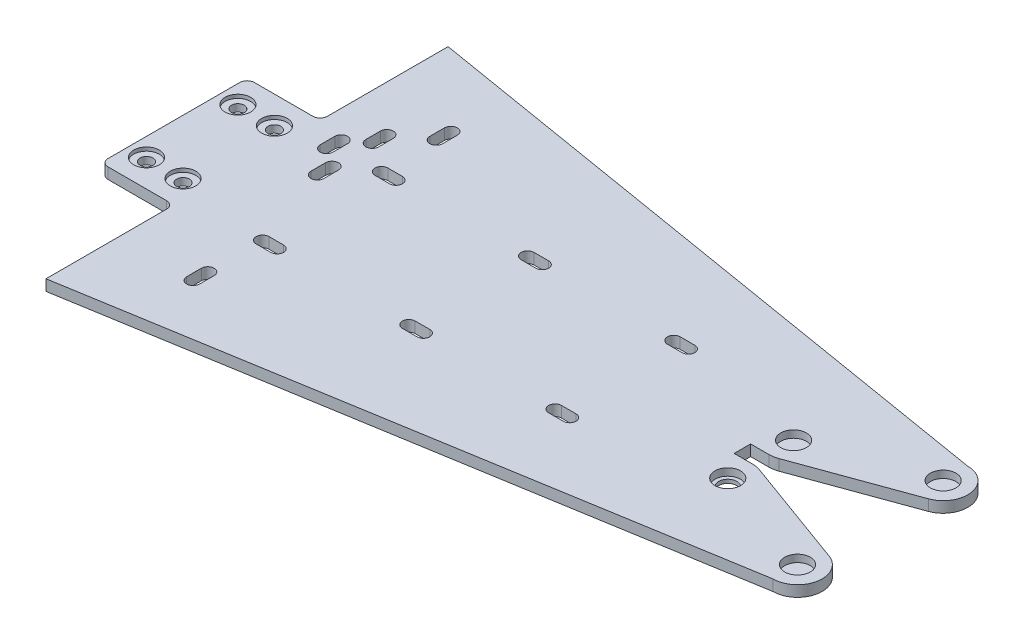
SolidWorks part; units mm, degrees
ref_plane "前视基准面" through (0, 0, 0) normal (0, 0, 1) x (1, 0, 0)
ref_plane "上视基准面" through (0, 0, 0) normal (0, 1, 0) x (1, 0, 0)
ref_plane "右视基准面" through (0, 0, 0) normal (1, 0, 0) x (0, 0, -1)
sketch "草图1" plane through (0, 0, 0) normal (0, 1, 0) x (1, 0, 0)
  line L1 (-17.5, -27.5) -> (17.5, -27.5)
  line L2 (-17.5, -27.5) -> (-17.5, 27.5)
  line L3 (-17.5, 27.5) -> (17.5, 27.5)
  line L4 (17.5, -27.5) -> (17.5, 27.5)
  line L5 (-17.5, -27.5) -> (17.5, 27.5) construction
  line L6 (-17.5, 27.5) -> (17.5, -27.5) construction
  point P0 (0, 0)
  dimension "D1" = 55
  dimension "D2" = 35
extrude "凸台-拉伸1" add sketch "草图1" along normal blind 1
sketch "草图2" plane through (0, 1, 0) normal (0, 1, 0) x (1, 0, 0)
  line L0 (-105.917, 0) -> (-62.25, 0) construction
  line L1 (106.75, 2.25) -> (121.75, 2.25)
  line L2 (-31.4474, 57.1013) -> (151.75, 26.6691)
  line L4 (124.0586, 2.6571) -> (154.0586, 13.5762)
  line L5 (-60.1618, 23.6059) -> (-42.6093, 52.0296)
  line L6 (121.75, 2.25) -> (121.75, 9) construction
  line L7 (121.75, -2.25) -> (121.75, -9) construction
  line L8 (-60.1618, -23.6059) -> (-42.6093, -52.0296)
  line L9 (124.0586, -2.6571) -> (154.0586, -13.5762)
  line L10 (121.75, -9) -> (128.5, -9)
  line L11 (-31.4474, -57.1013) -> (151.75, -26.6691)
  line L12 (106.75, -2.25) -> (121.75, -2.25)
  line L13 (-62.25, 16.25) -> (-62.25, -16.25)
  line L14 (106.75, 2.25) -> (106.75, -2.25)
  line L15 (106.75, 0) -> (124.0666, 0) construction
  arc A0 (-60.1618, 23.6059) -> (-62.25, 16.25) centre (-48.25, 16.25) ccw
  arc A1 (-31.4474, 57.1013) -> (-42.6093, 52.0296) centre (-33.25, 46.25) ccw
  arc A2 (121.75, 2.25) -> (124.0586, 2.6571) centre (121.75, 9) ccw
  arc A3 (154.0586, 13.5762) -> (151.75, 26.6691) centre (151.75, 19.9191) ccw
  arc A4 (154.0586, -13.5762) -> (151.75, -26.6691) centre (151.75, -19.9191) cw
  arc A5 (121.75, -2.25) -> (128.5, -9) centre (121.75, -9) cw
  arc A6 (-31.4474, -57.1013) -> (-42.6093, -52.0296) centre (-33.25, -46.25) cw
  arc A7 (-60.1618, -23.6059) -> (-62.25, -16.25) centre (-48.25, -16.25) cw
  dimension "D2" = 28
  dimension "D3" = 48.25
  dimension "D4" = 22
  dimension "D5" = 15
  dimension "D7" = 13.5
  dimension "D10" = 13.5
  dimension "D11" = 30
  dimension "D1" = 2.25
  dimension "D8" = 20
  dimension "D9" = 30
  dimension "D12" = 15
extrude "凸台-拉伸2" add sketch "草图2" along normal blind 3
sketch "草图3" plane through (0, 4, 0) normal (0, 1, 0) x (1, 0, 0)
  circle A0 centre (-48.25, 16.25) radius 5
  circle A1 centre (-48.25, -16.25) radius 5
  circle A2 centre (-33.25, 46.25) radius 6.6982
  circle A3 centre (151.75, 19.9191) radius 2.5794
  circle A4 centre (121.75, 9) radius 2.5794
  circle A5 centre (121.75, -9) radius 2.5794
  circle A6 centre (151.75, -19.9191) radius 2.5794
  circle A7 centre (-33.25, -46.25) radius 6.6982
  dimension "D1" = 10
extrude "切除-拉伸1" cut sketch "草图3" against normal through all contours A0 | A1
sketch "草图4" plane through (0, 4, 0) normal (0, 1, 0) x (1, 0, 0)
  circle A0 centre (-33.25, 46.25) radius 4
  circle A1 centre (-33.25, -46.25) radius 4
  dimension "D1" = 8
  dimension "D2" = 8
extrude "切除-拉伸2" cut sketch "草图4" against normal blind 2
sketch "草图5" plane through (0, 4, 0) normal (0, 1, 0) x (1, 0, 0)
  circle A0 centre (121.75, 9) radius 2
  circle A1 centre (121.75, -9) radius 2
  circle A2 centre (151.75, 19.9191) radius 2
  circle A3 centre (151.75, -19.9191) radius 2
  dimension "D1" = 4
extrude "切除-拉伸3" cut sketch "草图5" against normal blind 2
sketch "草图8" plane through (0, 1, 0) normal (0, -1, 0) x (1, 0, 0)
  line L1 (-39.75, -26.25) -> (-26.75, -26.25)
  line L2 (-39.75, -26.25) -> (-39.75, -66.25)
  line L3 (-39.75, -66.25) -> (-26.75, -66.25)
  line L4 (-26.75, -26.25) -> (-26.75, -66.25)
  line L5 (-39.75, -26.25) -> (-26.75, -66.25) construction
  line L6 (-39.75, -66.25) -> (-26.75, -26.25) construction
  line L16 (124.0586, 2.6571) -> (154.0586, 13.5762)
  line L17 (151.75, 26.6691) -> (-31.4474, 57.1013)
  line L18 (-42.6093, 52.0296) -> (-60.1618, 23.6059)
  line L19 (-62.25, 16.25) -> (-62.25, -16.25)
  line L20 (-60.1618, -23.6059) -> (-42.6093, -52.0296)
  line L21 (-31.4474, -57.1013) -> (151.75, -26.6691)
  line L22 (154.0586, -13.5762) -> (124.0586, -2.6571)
  line L23 (121.75, -2.25) -> (106.75, -2.25)
  line L24 (106.75, -2.25) -> (106.75, 2.25)
  line L25 (106.75, 2.25) -> (121.75, 2.25)
  line L26 (124.0586, 2.6571) -> (154.0586, 13.5762)
  line L27 (151.75, 26.6691) -> (-31.4474, 57.1013)
  line L28 (-42.6093, 52.0296) -> (-60.1618, 23.6059)
  line L31 (-31.4474, -57.1013) -> (151.75, -26.6691)
  line L32 (154.0586, -13.5762) -> (124.0586, -2.6571)
  line L33 (121.75, -2.25) -> (106.75, -2.25)
  line L34 (106.75, -2.25) -> (106.75, 2.25)
  line L35 (106.75, 2.25) -> (121.75, 2.25)
  arc A8 (154.0586, 13.5762) -> (151.75, 26.6691) centre (151.75, 19.9191) ccw
  arc A9 (-31.4474, 57.1013) -> (-42.6093, 52.0296) centre (-33.25, 46.25) ccw
  arc A10 (-60.1618, 23.6059) -> (-62.25, 16.25) centre (-48.25, 16.25) ccw
  arc A11 (-62.25, -16.25) -> (-60.1618, -23.6059) centre (-48.25, -16.25) ccw
  arc A12 (-42.6093, -52.0296) -> (-31.4474, -57.1013) centre (-33.25, -46.25) ccw
  arc A13 (151.75, -26.6691) -> (154.0586, -13.5762) centre (151.75, -19.9191) ccw
  arc A14 (124.0586, -2.6571) -> (121.75, -2.25) centre (121.75, -9) ccw
  arc A15 (121.75, 2.25) -> (124.0586, 2.6571) centre (121.75, 9) ccw
  arc A16 (154.0586, 13.5762) -> (151.75, 26.6691) centre (151.75, 19.9191) ccw
  arc A17 (-31.4474, 57.1013) -> (-42.6093, 52.0296) centre (-33.25, 46.25) ccw
  arc A18 (-60.1618, 23.6059) -> (-62.25, 16.25) centre (-48.25, 16.25) ccw
  arc A19 (-62.25, -16.25) -> (-60.1618, -23.6059) centre (-48.25, -16.25) ccw
  arc A20 (-42.6093, -52.0296) -> (-31.4474, -57.1013) centre (-33.25, -46.25) ccw
  arc A21 (151.75, -26.6691) -> (154.0586, -13.5762) centre (151.75, -19.9191) ccw
  arc A22 (124.0586, -2.6571) -> (121.75, -2.25) centre (121.75, -9) ccw
  arc A23 (121.75, 2.25) -> (124.0586, 2.6571) centre (121.75, 9) ccw
  point P0 (-33.25, -46.25)
  arc M32 (-42.6093, -52.0296) -> (-31.4474, -57.1013) centre (-33.25, -46.25) ccw
  line M33 (-31.4474, -57.1013) -> (151.75, -26.6691)
  dimension "D1" = 13
  dimension "D2" = 40
  dimension "D3" = 0
extrude "凸台-拉伸3" add sketch "草图8" along normal blind 7 contours L4 L1 L2 M32 M33
mirror "镜向1" about plane through (0, 0, 0) normal (0, 0, 1) of "凸台-拉伸3"
sketch "草图9" plane through (0, -6, 0) normal (0, -1, 0) x (1, 0, 0)
  line L0 (-39.75, -26.25) -> (-26.75, -26.25) construction
  line L2 (-38.25, -53.75) -> (-38.25, -27.75)
  line L3 (-38.25, -27.75) -> (-28.25, -27.75)
  line L4 (-28.25, -53.75) -> (-28.25, -27.75)
  line L5 (-35.5448, -54.7408) -> (-28.25, -27.75) construction
  line L6 (-38.25, -27.75) -> (-31.223, -53.75) construction
  line L8 (-28.25, -53.75) -> (-38.25, -53.75)
  point P0 (-33.25, -46.25)
  dimension "D1" = 10
  dimension "D2" = 1.5
  dimension "D3" = 26
extrude "切除-拉伸4" cut sketch "草图9" against normal through all from offset 1.5 offset against normal yes
mirror "镜向2" about plane through (0, 0, 0) normal (0, 0, 1) of "切除-拉伸4"
sketch "草图10" plane through (0, 0, -53.75) normal (0, 0, 1) x (1, 0, 0)
  line L4 (-38.25, -4.5) -> (-28.25, -4.5)
  line L5 (-28.25, -4.5) -> (-28.25, 4)
  line L6 (-28.25, 4) -> (-38.25, 4)
  line L7 (-38.25, 4) -> (-38.25, -4.5)
  line L8 (-38.25, -4.5) -> (-28.25, -4.5)
  line L9 (-28.25, -4.5) -> (-28.25, 4)
  line L10 (-28.25, 4) -> (-38.25, 4)
  line L11 (-38.25, 4) -> (-38.25, -4.5)
  circle A0 centre (-33.25, -1.5) radius 1.5
  dimension "D2" = 3
  dimension "D3" = 3
  dimension "D1" = 0
extrude "切除-拉伸5" cut sketch "草图10" against normal through all contours A0
mirror "镜向3" about plane through (0, 0, 0) normal (0, 0, 1) of "切除-拉伸5"
sketch "草图11" plane through (0, 4, 0) normal (0, 1, 0) x (1, 0, 0)
  line L0 (-62.25, 16.25) -> (-62.25, 50.4199)
  line L1 (-62.25, -16.25) -> (-62.25, -50.4199)
  line L10 (154.0586, -13.5762) -> (124.0586, -2.6571)
  line L11 (121.75, -2.25) -> (106.75, -2.25)
  line L12 (106.75, -2.25) -> (106.75, 2.25)
  line L13 (106.75, 2.25) -> (121.75, 2.25)
  line L14 (124.0586, 2.6571) -> (154.0586, 13.5762)
  line L15 (151.75, 26.6691) -> (-31.4474, 57.1013)
  line L16 (-42.6093, 52.0296) -> (-60.1618, 23.6059)
  line L17 (-62.25, 16.25) -> (-62.25, -16.25)
  line L18 (-60.1618, -23.6059) -> (-42.6093, -52.0296)
  line L19 (-31.4474, -57.1013) -> (151.75, -26.6691)
  line L20 (154.0586, -13.5762) -> (124.0586, -2.6571)
  line L21 (121.75, -2.25) -> (106.75, -2.25)
  line L22 (106.75, -2.25) -> (106.75, 2.25)
  line L23 (106.75, 2.25) -> (121.75, 2.25)
  line L24 (124.0586, 2.6571) -> (154.0586, 13.5762)
  line L25 (151.75, 26.6691) -> (-50.6113, 60.2847)
  line L26 (-42.6093, 52.0296) -> (-60.1618, 23.6059)
  line L27 (-62.25, 16.25) -> (-62.25, -16.25)
  line L28 (-60.1618, -23.6059) -> (-42.6093, -52.0296)
  line L29 (-50.6113, -60.2847) -> (151.75, -26.6691)
  arc A0 (-62.25, -50.4199) -> (-50.6113, -60.2847) centre (-52.25, -50.4199) ccw
  arc A1 (-50.6113, 60.2847) -> (-62.25, 50.4199) centre (-52.25, 50.4199) ccw
  arc A8 (124.0586, -2.6571) -> (121.75, -2.25) centre (121.75, -9) ccw
  arc A9 (121.75, 2.25) -> (124.0586, 2.6571) centre (121.75, 9) ccw
  arc A10 (154.0586, 13.5762) -> (151.75, 26.6691) centre (151.75, 19.9191) ccw
  arc A11 (-31.4474, 57.1013) -> (-42.6093, 52.0296) centre (-33.25, 46.25) ccw
  arc A12 (-60.1618, 23.6059) -> (-62.25, 16.25) centre (-48.25, 16.25) ccw
  arc A13 (-62.25, -16.25) -> (-60.1618, -23.6059) centre (-48.25, -16.25) ccw
  arc A14 (-42.6093, -52.0296) -> (-31.4474, -57.1013) centre (-33.25, -46.25) ccw
  arc A15 (151.75, -26.6691) -> (154.0586, -13.5762) centre (151.75, -19.9191) ccw
  arc A16 (124.0586, -2.6571) -> (121.75, -2.25) centre (121.75, -9) ccw
  arc A17 (121.75, 2.25) -> (124.0586, 2.6571) centre (121.75, 9) ccw
  arc A18 (154.0586, 13.5762) -> (151.75, 26.6691) centre (151.75, 19.9191) ccw
  arc A19 (-31.4474, 57.1013) -> (-42.6093, 52.0296) centre (-33.25, 46.25) ccw
  arc A20 (-60.1618, 23.6059) -> (-62.25, 16.25) centre (-48.25, 16.25) ccw
  arc A21 (-62.25, -16.25) -> (-60.1618, -23.6059) centre (-48.25, -16.25) ccw
  arc A22 (-42.6093, -52.0296) -> (-31.4474, -57.1013) centre (-33.25, -46.25) ccw
  arc A23 (151.75, -26.6691) -> (154.0586, -13.5762) centre (151.75, -19.9191) ccw
  arc M28 (-31.4474, 57.1013) -> (-42.6093, 52.0296) centre (-33.25, 46.25) ccw
  line M29 (-42.6093, 52.0296) -> (-60.1618, 23.6059)
  arc M30 (-60.1618, 23.6059) -> (-62.25, 16.25) centre (-48.25, 16.25) ccw
  arc M32 (-62.25, -16.25) -> (-60.1618, -23.6059) centre (-48.25, -16.25) ccw
  line M33 (-60.1618, -23.6059) -> (-42.6093, -52.0296)
  arc M34 (-42.6093, -52.0296) -> (-31.4474, -57.1013) centre (-33.25, -46.25) ccw
  dimension "D2" = 10
  dimension "D3" = 10
  dimension "D1" = 0
extrude "凸台-拉伸4" add sketch "草图11" against normal up to surface (3 mm away) contours L25 A1 L0 M30 M29 M28 | L1 A0 L29 M34 M33 M32 up to face at (0, 1, 0)
sketch "草图12" plane through (0, 1, 0) normal (0, -1, 0) x (1, 0, 0)
  circle A0 centre (-48.25, 16.25) radius 9
  circle A1 centre (-48.25, -16.25) radius 9
  circle A2 centre (-48.25, 16.25) radius 5 construction
  circle A3 centre (-48.25, 16.25) radius 5
  circle A4 centre (-48.25, -16.25) radius 5 construction
  circle A5 centre (-48.25, -16.25) radius 5
  dimension "D1" = 18
  dimension "D2" = 18
extrude "凸台-拉伸5" add sketch "草图12" along normal blind 2.5
sketch "草图13" plane through (0, 4, 0) normal (0, 1, 0) x (1, 0, 0)
  circle A0 centre (-48.25, 16.25) radius 7.5
  circle A1 centre (-48.25, -16.25) radius 7.5
  dimension "D1" = 15
  dimension "D2" = 15
extrude "切除-拉伸6" cut sketch "草图13" against normal blind 4
sketch "草图14" plane through (0, 4, 0) normal (0, 1, 0) x (1, 0, 0)
  line L0 (-45.75, 61.25) -> (-45.75, 27.75)
  line L2 (-20.75, 27.75) -> (-20.75, 61.25)
  line L3 (-20.75, 61.25) -> (-45.75, 61.25)
  line L4 (-28.25, 27.75) -> (-28.25, 53.75)
  line L5 (-28.25, 53.75) -> (-38.25, 53.75)
  line L6 (-38.25, 53.75) -> (-38.25, 27.75)
  line L7 (-38.25, 27.75) -> (-28.25, 27.75)
  line L8 (-28.25, 27.75) -> (-28.25, 53.75)
  line L9 (-28.25, 53.75) -> (-38.25, 53.75)
  line L10 (-38.25, 53.75) -> (-38.25, 27.75)
  line L11 (-45.75, 27.75) -> (-20.75, 27.75)
  line L12 (-38.25, 27.75) -> (-28.25, 27.75) construction
  line L13 (-45.75, 61.25) -> (-45.75, 20.25) construction
  line L14 (-20.75, 20.25) -> (-20.75, 61.25) construction
  line L15 (-45.75, 20.25) -> (-20.75, 20.25) construction
  line M19 (151.75, 26.6691) -> (-50.6113, 60.2847)
  line M25 (-28.25, 53.75) -> (-28.25, 27.75)
  line M26 (-28.25, 27.75) -> (-38.25, 27.75)
  line M27 (-38.25, 27.75) -> (-38.25, 53.75)
  line M28 (-38.25, 53.75) -> (-28.25, 53.75)
  dimension "D1" = 0
  dimension "D2" = 7.5
extrude "切除-拉伸7" cut sketch "草图14" against normal blind 2 contours M25 M28 M27 M26 | L0 L11 L2 M27 M28 M25 M19
sketch "草图15" plane through (0, 2, 0) normal (0, 1, 0) x (1, 0, 0)
  line L8 (-28.25, 53.75) -> (-28.25, 27.75)
  line L9 (-28.25, 27.75) -> (-20.75, 27.75)
  line L10 (-20.75, 27.75) -> (-20.75, 55.3243)
  line L11 (-20.75, 55.3243) -> (-45.75, 59.4772)
  line L12 (-45.75, 59.4772) -> (-45.75, 27.75)
  line L13 (-45.75, 27.75) -> (-38.25, 27.75)
  line L14 (-38.25, 27.75) -> (-38.25, 53.75)
  line L15 (-38.25, 53.75) -> (-28.25, 53.75)
  line L19 (-18.75, 54.992) -> (-47.75, 59.8094)
  line L23 (-38.25, 53.75) -> (-28.25, 53.75)
  line L32 (-30.25, 51.75) -> (-30.25, 25.75)
  line L33 (-30.25, 25.75) -> (-18.75, 25.75)
  line L34 (-18.75, 25.75) -> (-18.75, 57.0195)
  line L35 (-18.75, 57.0195) -> (-47.75, 61.8368)
  line L36 (-47.75, 61.8368) -> (-47.75, 25.75)
  line L37 (-47.75, 25.75) -> (-36.25, 25.75)
  line L38 (-36.25, 25.75) -> (-36.25, 51.75)
  line L39 (-36.25, 51.75) -> (-30.25, 51.75)
  line L41 (-30.25, 25.75) -> (-18.75, 25.75)
  line L42 (-18.75, 25.75) -> (-18.75, 54.992)
  line L44 (-47.75, 59.8094) -> (-47.75, 25.75)
  line L45 (-47.75, 25.75) -> (-30.25, 25.75)
  dimension "D1" = 0
  dimension "D2" = 2
extrude "凸台-拉伸6" add sketch "草图15" against normal blind 2 from surface at -1 contours L44 L45 L41 L42 L19 starting at face at (-48.25, 1, 25.25)
sketch "草图16" plane through (0, -6, 0) normal (0, -1, 0) x (1, 0, 0)
  line L0 (-39.75, -55.1241) -> (-39.75, -65.9532)
  line L1 (-39.75, -65.9532) -> (-26.75, -64.7485)
  line L2 (-26.75, -64.7485) -> (-26.75, -56.321)
  line L4 (-26.75, -56.321) -> (-26.75, -26.25)
  line L5 (-26.75, -26.25) -> (-39.75, -26.25)
  line L6 (-39.75, -26.25) -> (-39.75, -55.1241)
  line L7 (-31.4474, -57.1013) -> (-26.75, -56.321)
  line L8 (-26.75, -56.321) -> (-26.75, -26.25)
  line L9 (-26.75, -26.25) -> (-39.75, -26.25)
  line L10 (-39.75, -26.25) -> (-39.75, -55.1241)
  line L11 (-31.4474, -57.1013) -> (-26.75, -56.321)
  arc A1 (-39.75, -55.1241) -> (-31.4474, -57.1013) centre (-33.25, -46.25) ccw
  arc A2 (-39.75, -55.1241) -> (-31.4474, -57.1013) centre (-33.25, -46.25) ccw
  line M6 (-26.75, -56.321) -> (-26.75, -26.25)
  line M7 (-26.75, -26.25) -> (-39.75, -26.25)
  line M8 (-39.75, -26.25) -> (-39.75, -55.1241)
  arc M9 (-39.75, -55.1241) -> (-31.4474, -57.1013) centre (-33.25, -46.25) ccw
  line M10 (-31.4474, -57.1013) -> (-26.75, -56.321)
  dimension "D1" = 0
extrude "切除-拉伸8" cut sketch "草图16" against normal through all contours M10 M6 M7 M8 M9 | L1 L2 L0 M10 M9
mirror "镜向4" about plane through (0, 0, 0) normal (0, 0, 1) of "切除-拉伸7", "切除-拉伸4", "凸台-拉伸6", "切除-拉伸8"
sketch "草图17" plane through (0, 0, 0) normal (0, -1, 0) x (1, 0, 0)
  line L4 (17.5, -27.5) -> (17.5, 27.5)
  line L5 (17.5, 27.5) -> (-17.5, 27.5)
  line L6 (-17.5, 27.5) -> (-17.5, -27.5)
  line L7 (-17.5, -27.5) -> (17.5, -27.5)
  line L8 (17.5, -27.5) -> (17.5, 27.5)
  line L9 (17.5, 27.5) -> (-17.5, 27.5)
  line L10 (-17.5, 27.5) -> (-17.5, -27.5)
  line L11 (-17.5, -27.5) -> (17.5, -27.5)
  dimension "D1" = 0
extrude "切除-拉伸9" cut sketch "草图17" against normal up to surface (1 mm away) up to face at (-48.25, 1, -7.25)
sketch "草图19" plane through (0, 1, 0) normal (0, -1, 0) x (1, 0, 0)
  line L8 (-47.75, -59.8094) -> (-39.75, -58.4805)
  line L9 (-39.75, -58.4805) -> (-39.75, -26.25)
  line L10 (-39.75, -26.25) -> (-26.75, -26.25)
  line L11 (-26.75, -26.25) -> (-26.75, -56.321)
  line L12 (-26.75, -56.321) -> (-18.75, -54.992)
  line L13 (-18.75, -54.992) -> (-18.75, -25.75)
  line L14 (-18.75, -25.75) -> (-47.75, -25.75)
  line L15 (-47.75, -25.75) -> (-47.75, -59.8094)
  line L16 (-18.75, 54.992) -> (-18.75, 25.75)
  line L17 (-18.75, 25.75) -> (-47.75, 25.75)
  line L18 (-47.75, 25.75) -> (-47.75, 59.8094)
  line L19 (-47.75, 59.8094) -> (-50.6113, 60.2847)
  line L20 (-62.25, 50.4199) -> (-62.25, -50.4199)
  line L21 (-50.6113, -60.2847) -> (-47.75, -59.8094)
  line L22 (-47.75, -59.8094) -> (-47.75, -25.75)
  line L23 (-47.75, -25.75) -> (-18.75, -25.75)
  line L24 (-18.75, -25.75) -> (-18.75, -54.992)
  line L25 (-18.75, -54.992) -> (151.75, -26.6691)
  line L26 (154.0586, -13.5762) -> (124.0586, -2.6571)
  line L27 (121.75, -2.25) -> (106.75, -2.25)
  line L28 (106.75, -2.25) -> (106.75, 2.25)
  line L29 (106.75, 2.25) -> (121.75, 2.25)
  line L30 (124.0586, 2.6571) -> (154.0586, 13.5762)
  line L31 (151.75, 26.6691) -> (-18.75, 54.992)
  line L32 (-18.75, 54.992) -> (-18.75, -25.75)
  line L35 (-47.75, 59.8094) -> (-50.6113, 60.2847)
  line L36 (-62.25, 50.4199) -> (-62.25, -50.4199)
  line L37 (-50.6113, -60.2847) -> (-47.75, -59.8094)
  line L40 (-18.75, -25.75) -> (-18.75, -54.992)
  line L48 (-47.75, -59.8094) -> (-39.75, -58.4805)
  line L49 (-39.75, -58.4805) -> (-39.75, -26.25)
  line L50 (-39.75, -26.25) -> (-26.75, -26.25)
  line L51 (-26.75, -26.25) -> (-26.75, -56.321)
  line L52 (-26.75, -56.321) -> (-18.75, -54.992)
  line L53 (-18.75, -54.992) -> (-18.75, -25.75)
  line L56 (-39.75, 26.25) -> (-39.75, 58.4805)
  line L57 (-39.75, 58.4805) -> (-47.75, 59.8094)
  line L58 (-47.75, 59.8094) -> (-47.75, 25.75)
  line L59 (-47.75, 25.75) -> (-18.75, 25.75)
  line L60 (-18.75, 25.75) -> (-18.75, 54.992)
  line L61 (-18.75, 54.992) -> (-26.75, 56.321)
  line L62 (-26.75, 56.321) -> (-26.75, 26.25)
  line L63 (-26.75, 26.25) -> (-39.75, 26.25)
  line L64 (-39.75, 26.25) -> (-39.75, 58.4805)
  line L65 (-39.75, 58.4805) -> (-47.75, 59.8094)
  line L68 (-18.75, 25.75) -> (-18.75, 54.992)
  line L69 (-18.75, 54.992) -> (-26.75, 56.321)
  line L70 (-26.75, 56.321) -> (-26.75, 26.25)
  line L71 (-26.75, 26.25) -> (-39.75, 26.25)
  circle A0 centre (-48.25, 16.25) radius 5 construction
  circle A1 centre (-48.25, 16.25) radius 5
  circle A2 centre (-48.25, -16.25) radius 5 construction
  circle A3 centre (-48.25, -16.25) radius 5
  arc A6 (-50.6113, 60.2847) -> (-62.25, 50.4199) centre (-52.25, 50.4199) ccw
  arc A7 (-62.25, -50.4199) -> (-50.6113, -60.2847) centre (-52.25, -50.4199) ccw
  arc A8 (151.75, -26.6691) -> (154.0586, -13.5762) centre (151.75, -19.9191) ccw
  arc A9 (124.0586, -2.6571) -> (121.75, -2.25) centre (121.75, -9) ccw
  arc A10 (121.75, 2.25) -> (124.0586, 2.6571) centre (121.75, 9) ccw
  arc A11 (154.0586, 13.5762) -> (151.75, 26.6691) centre (151.75, 19.9191) ccw
  arc A12 (-50.6113, 60.2847) -> (-62.25, 50.4199) centre (-52.25, 50.4199) ccw
  arc A13 (-62.25, -50.4199) -> (-50.6113, -60.2847) centre (-52.25, -50.4199) ccw
  circle M23 centre (-48.25, -16.25) radius 9
  circle M24 centre (-48.25, 16.25) radius 9
  line M25 (-18.75, 54.992) -> (-18.75, 25.75)
  line M26 (-18.75, 25.75) -> (-47.75, 25.75)
  line M27 (-47.75, 25.75) -> (-47.75, 59.8094)
  line M28 (-47.75, 59.8094) -> (-50.6113, 60.2847)
  arc M29 (-50.6113, 60.2847) -> (-62.25, 50.4199) centre (-52.25, 50.4199) ccw
  line M30 (-62.25, 50.4199) -> (-62.25, -50.4199)
  arc M31 (-62.25, -50.4199) -> (-50.6113, -60.2847) centre (-52.25, -50.4199) ccw
  line M32 (-50.6113, -60.2847) -> (-47.75, -59.8094)
  line M33 (-47.75, -59.8094) -> (-47.75, -25.75)
  line M34 (-47.75, -25.75) -> (-18.75, -25.75)
  line M35 (-18.75, -25.75) -> (-18.75, -54.992)
  dimension "D1" = 0
  dimension "D2" = 0
  dimension "D3" = 0
extrude "凸台-拉伸8" add sketch "草图19" along direction (0, -1, 0) on the side of the normal up to surface (2.5 mm away) contours L32 M26 M27 M28 M29 M30 M31 M32 M33 M34 M24 M23 | L70 L71 L64 L65 L69 M27 M26 M25 | L51 L52 L48 L49 L50 M35 M34 M33
sketch "草图20" plane through (0, 4, 0) normal (0, 1, 0) x (1, 0, 0)
  line L0 (-39.75, 27.75) -> (-26.75, 27.75)
  line L1 (-26.75, 27.75) -> (-26.75, 26.25)
  line L2 (-26.75, 26.25) -> (-39.75, 26.25)
  line L3 (-39.75, 26.25) -> (-39.75, 27.75) construction
  line L4 (-26.75, 26.25) -> (-39.75, 26.25) construction
  line L5 (-39.75, 26.25) -> (-39.75, 27.75)
  line L6 (-39.75, -26.25) -> (-39.75, -27.75)
  line L7 (-39.75, -27.75) -> (-26.75, -27.75)
  line L8 (-26.75, -27.75) -> (-26.75, -26.25)
  line L9 (-26.75, -26.25) -> (-39.75, -26.25)
  line M7 (-39.75, -26.25) -> (-26.75, -26.25)
  line M8 (-26.75, -26.25) -> (-26.75, -27.75)
  line M24 (-26.75, 27.75) -> (-26.75, 26.25)
  line M25 (-26.75, 26.25) -> (-39.75, 26.25)
  line M26 (-39.75, 26.25) -> (-39.75, 27.75)
  line M36 (-39.75, -27.75) -> (-39.75, -26.25)
extrude "凸台-拉伸9" add sketch "草图20" against normal up to surface (5.5 mm away) contours L0 M26 M25 M24 | L7 M36 M8 M7 up to face at (-48.25, -1.5, 11.25)
sketch "草图21" plane through (0, 4, 0) normal (0, 1, 0) x (1, 0, 0)
  circle A0 centre (121.75, 9) radius 3.5
  circle A1 centre (121.75, -9) radius 3.5
  circle A2 centre (151.75, -19.9191) radius 3.5
  circle A3 centre (151.75, 19.9191) radius 3.5
  dimension "D1" = 7
  dimension "D2" = 7
  dimension "D3" = 7
  dimension "D4" = 7
extrude "切除-拉伸10" cut sketch "草图21" against normal up to surface (2 mm away) up to face at (121.75, 2, -7)
sketch "草图22" plane through (0, 4, 0) normal (0, 1, 0) x (1, 0, 0)
  line L0 (-48.25, 16.25) -> (79.7875, 16.25)
  line L1 (1.75, 16.25) -> (5.75, 16.25) construction
  line L2 (1.75, 18) -> (5.75, 18)
  line L3 (1.75, 14.5) -> (5.75, 14.5)
  line L4 (41.75, 16.25) -> (45.75, 16.25) construction
  line L5 (41.75, 18) -> (45.75, 18)
  line L6 (41.75, 14.5) -> (45.75, 14.5)
  line L7 (81.75, 16.25) -> (85.75, 16.25) construction
  line L8 (81.75, 18) -> (85.75, 18)
  line L9 (81.75, 14.5) -> (85.75, 14.5)
  line L10 (1.75, 31.25) -> (1.75, 35.25) construction
  line L11 (0, 31.25) -> (0, 35.25)
  line L12 (3.5, 31.25) -> (3.5, 35.25)
  line L13 (-3.025, 0) -> (3.025, 0) construction
  line L14 (1.75, -16.25) -> (5.75, -16.25) construction
  line L15 (1.75, -18) -> (5.75, -18)
  line L16 (1.75, -14.5) -> (5.75, -14.5)
  line L17 (41.75, -16.25) -> (45.75, -16.25) construction
  line L18 (41.75, -18) -> (45.75, -18)
  line L19 (41.75, -14.5) -> (45.75, -14.5)
  line L20 (81.75, -16.25) -> (85.75, -16.25) construction
  line L21 (81.75, -18) -> (85.75, -18)
  line L22 (81.75, -14.5) -> (85.75, -14.5)
  line L23 (1.75, -31.25) -> (1.75, -35.25) construction
  line L24 (0, -31.25) -> (0, -35.25)
  line L25 (3.5, -31.25) -> (3.5, -35.25)
  arc A0 (1.75, 18) -> (1.75, 14.5) centre (1.75, 16.25) ccw
  arc A1 (5.75, 14.5) -> (5.75, 18) centre (5.75, 16.25) ccw
  arc A2 (41.75, 18) -> (41.75, 14.5) centre (41.75, 16.25) ccw
  arc A3 (45.75, 14.5) -> (45.75, 18) centre (45.75, 16.25) ccw
  arc A4 (81.75, 18) -> (81.75, 14.5) centre (81.75, 16.25) ccw
  arc A5 (85.75, 14.5) -> (85.75, 18) centre (85.75, 16.25) ccw
  arc A6 (0, 31.25) -> (3.5, 31.25) centre (1.75, 31.25) ccw
  arc A7 (3.5, 35.25) -> (0, 35.25) centre (1.75, 35.25) ccw
  arc A8 (1.75, -18) -> (1.75, -14.5) centre (1.75, -16.25) cw
  arc A9 (5.75, -14.5) -> (5.75, -18) centre (5.75, -16.25) cw
  arc A10 (41.75, -18) -> (41.75, -14.5) centre (41.75, -16.25) cw
  arc A11 (45.75, -14.5) -> (45.75, -18) centre (45.75, -16.25) cw
  arc A12 (81.75, -18) -> (81.75, -14.5) centre (81.75, -16.25) cw
  arc A13 (85.75, -14.5) -> (85.75, -18) centre (85.75, -16.25) cw
  arc A14 (0, -31.25) -> (3.5, -31.25) centre (1.75, -31.25) cw
  arc A15 (3.5, -35.25) -> (0, -35.25) centre (1.75, -35.25) cw
  point P5 (3.75, 16.25)
  point P10 (43.75, 16.25)
  point P17 (83.75, 16.25)
  point P26 (1.75, 33.25)
  point P35 (3.75, -16.25)
  point P42 (43.75, -16.25)
  point P49 (83.75, -16.25)
  point P56 (1.75, -33.25)
  dimension "D1" = 3.5
  dimension "D8" = 40
  dimension "D9" = 40
  dimension "D2" = 4
  dimension "D3" = 4
  dimension "D4" = 4
  dimension "D5" = 3.5
  dimension "D6" = 3.5
  dimension "D7" = 50
  dimension "D10" = 3.5
  dimension "D11" = 4
  dimension "D12" = 15
extrude "切除-拉伸11" cut sketch "草图22" against normal blind 10 contours A9 L16 A8 L15 | A13 L22 A12 L21 | L12 A7 L11 A6 | L3 A1 L0 A0 | L9 A5 L8 A4 | L0 A1 L2 A0 | L25 A15 L24 A14 | L18 A11 L19 A10 | L6 A3 L5 A2
sketch "草图23" plane through (0, 4, 0) normal (0, 1, 0) x (1, 0, 0)
  line L0 (-39.75, 27.75) -> (-45.75, 27.75)
  line L1 (-20.75, 27.75) -> (-45.75, 27.75) construction
  line L2 (-39.75, 27.75) -> (-45.75, 27.75) construction
  line L3 (-26.75, 27.75) -> (-20.75, 27.75)
  line L4 (-20.75, 27.75) -> (-26.75, 27.75) construction
  arc A0 (-50.6113, 60.2847) -> (-62.25, 50.4199) centre (-52.25, 50.4199) ccw construction
  arc A1 (-50.6113, 60.2847) -> (-62.25, 50.4199) centre (-52.25, 50.4199) ccw
  circle A2 centre (-48.25, 16.25) radius 5 construction
  circle A3 centre (-42.75, 32.75) radius 1.75
  circle A4 centre (-23.75, 32.75) radius 1.75
  circle A5 centre (-23.75, 42.75) radius 1.75
  circle A6 centre (-42.75, 42.75) radius 1.75
  dimension "D2" = 3.5
  dimension "D3" = 3.5
  dimension "D4" = 3.5
  dimension "D5" = 3.5
  dimension "D6" = 5
  dimension "D7" = 10
  dimension "D8" = 10
  dimension "D9" = 5
  dimension "D1" = 34.1699
extrude "切除-拉伸12" cut sketch "草图23" against normal blind 10 contours A6 | A3 | A4 | A5
mirror "镜向5" about plane through (0, 0, 0) normal (0, 0, 1) of "切除-拉伸12"
sketch "草图25" plane through (0, 4, 0) normal (0, 1, 0) x (1, 0, 0)
  circle A0 centre (-52.25, -50.4199) radius 1.75
  circle A1 centre (-52.25, 50.4199) radius 1.75
  dimension "D1" = 3.5
  dimension "D2" = 3.5
extrude "切除-拉伸14" cut sketch "草图25" against normal through all
sketch "草图29" plane through (-18.75, 0, 0) normal (1, 0, 0) x (0, 0, -1)
  line L1 (-71.3913, 15.948) -> (97.3385, 15.948)
  line L2 (-71.3913, 15.948) -> (-71.3913, -21.8733)
  line L3 (-71.3913, -21.8733) -> (97.3385, -21.8733)
  line L4 (97.3385, 15.948) -> (97.3385, -21.8733)
extrude "切除-拉伸16" cut sketch "草图29" against normal through all
sketch "草图30" plane through (-18.75, 0, 0) normal (-1, 0, 0) x (0, 0, 1)
  line L0 (54.992, 4) -> (-54.992, 4) construction
  line L1 (-20, 4) -> (20, 4)
  line L2 (-20, 4) -> (-20, 1)
  line L3 (54.992, 1) -> (-54.992, 1) construction
  line L4 (-20, 1) -> (20, 1)
  line L5 (20, 1) -> (20, 4)
  point P0 (0, 4)
  point P6 (0, 4)
  dimension "D1" = 40
extrude "凸台-拉伸10" add sketch "草图30" along normal blind 20
sketch "草图31" plane through (0, 4, 0) normal (0, 1, 0) x (1, 0, 0)
  line L0 (-38.75, 0) -> (-14.4988, 0)
  line L1 (-38.75, -20) -> (-38.75, 20) construction
  line L2 (-1.65, 0) -> (1.65, 0) construction
  line L3 (-18.75, 20) -> (-18.75, 54.992) construction
  line L4 (-33.75, -12.5) -> (-23.75, -12.5)
  line L5 (-33.75, -12.5) -> (-33.75, 12.5)
  line L6 (-33.75, 12.5) -> (-23.75, 12.5)
  line L7 (-23.75, -12.5) -> (-23.75, 12.5)
  line L8 (-33.75, -12.5) -> (-23.75, 12.5) construction
  line L9 (-33.75, 12.5) -> (-23.75, -12.5) construction
  circle A0 centre (-33.75, 12.5) radius 1.75
  circle A1 centre (-23.75, 12.5) radius 1.75
  circle A2 centre (-23.75, -12.5) radius 1.75
  circle A3 centre (-33.75, -12.5) radius 1.75
  point P7 (-28.75, 0)
  dimension "D1" = 3.5
  dimension "D2" = 10
  dimension "D3" = 5
  dimension "D4" = 25
extrude "切除-拉伸17" cut sketch "草图31" against normal blind 10 contours L6 A1 L7 | L7 A1 L6 | L5 A0 L6 | L6 A0 L5 | L4 A2 L7 | L7 A2 L4 | L5 A3 L4 | L4 A3 L5
sketch "草图32" plane through (0, 4, 0) normal (0, 1, 0) x (1, 0, 0)
  circle A0 centre (-23.75, 12.5) radius 3.5
  circle A1 centre (-33.75, 12.5) radius 3.5
  circle A2 centre (-33.75, -12.5) radius 3.5
  circle A3 centre (-23.75, -12.5) radius 3.5
  dimension "D1" = 7
extrude "切除-拉伸18" cut sketch "草图32" against normal blind 1
sketch "草图33" plane through (0, 2, 0) normal (0, 1, 0) x (1, 0, 0)
  circle A0 centre (121.75, -9) radius 2.5
  dimension "D1" = 5
extrude "切除-拉伸19" cut sketch "草图33" against normal blind 1
sketch "草图34" plane through (0, 4, 0) normal (0, 1, 0) x (1, 0, 0)
  line L0 (7.5, 16.25) -> (-16.18, 16.25) construction
  line L1 (-11.25, 14.25) -> (-11.25, 18.25) construction
  line L2 (-13, 14.25) -> (-13, 18.25)
  line L3 (-9.5, 14.25) -> (-9.5, 18.25)
  line L4 (-6.25, 21.75) -> (-6.25, 25.75) construction
  line L5 (-8, 21.75) -> (-8, 25.75)
  line L6 (-4.5, 21.75) -> (-4.5, 25.75)
  line L7 (-6.25, 6.75) -> (-6.25, 10.75) construction
  line L8 (-8, 6.75) -> (-8, 10.75)
  line L9 (-4.5, 6.75) -> (-4.5, 10.75)
  line L10 (0, -1.65) -> (0, 1.65) construction
  arc A0 (5.75, 14.5) -> (5.75, 18) centre (5.75, 16.25) ccw construction
  arc A1 (-13, 14.25) -> (-9.5, 14.25) centre (-11.25, 14.25) ccw
  arc A2 (-9.5, 18.25) -> (-13, 18.25) centre (-11.25, 18.25) ccw
  arc A3 (-8, 21.75) -> (-4.5, 21.75) centre (-6.25, 21.75) ccw
  arc A4 (-4.5, 25.75) -> (-8, 25.75) centre (-6.25, 25.75) ccw
  arc A5 (-8, 6.75) -> (-4.5, 6.75) centre (-6.25, 6.75) ccw
  arc A6 (-4.5, 10.75) -> (-8, 10.75) centre (-6.25, 10.75) ccw
  point P8 (-11.25, 16.25)
  point P14 (-6.25, 23.75)
  point P21 (-6.25, 8.75)
  dimension "D1" = 1.75
  dimension "D2" = 4
  dimension "D3" = 5
  dimension "D4" = 6.25
  dimension "D5" = 15
  dimension "D6" = 7.5
extrude "切除-拉伸21" cut sketch "草图34" against normal through all
sketch "草图35" plane through (106.75, 0, 0) normal (1, 0, 0) x (0, 0, -1)
  line L4 (-2.25, 1) -> (2.25, 1)
  line L5 (2.25, 1) -> (2.25, 4)
  line L6 (2.25, 4) -> (-2.25, 4)
  line L7 (-2.25, 4) -> (-2.25, 1)
  line L8 (-2.25, 1) -> (2.25, 1)
  line L9 (2.25, 1) -> (2.25, 4)
  line L10 (2.25, 4) -> (-2.25, 4)
  line L11 (-2.25, 4) -> (-2.25, 1)
  dimension "D1" = 0
extrude "凸台-拉伸11" add sketch "草图35" along normal blind 10
fillet "圆角1" radius 2 2 edges at (-38.75, 2.5, 20) (-38.75, 2.5, -20)
fillet "圆角2" radius 2 2 edges at (-18.75, 2.5, 20) (-18.75, 2.5, -20)
